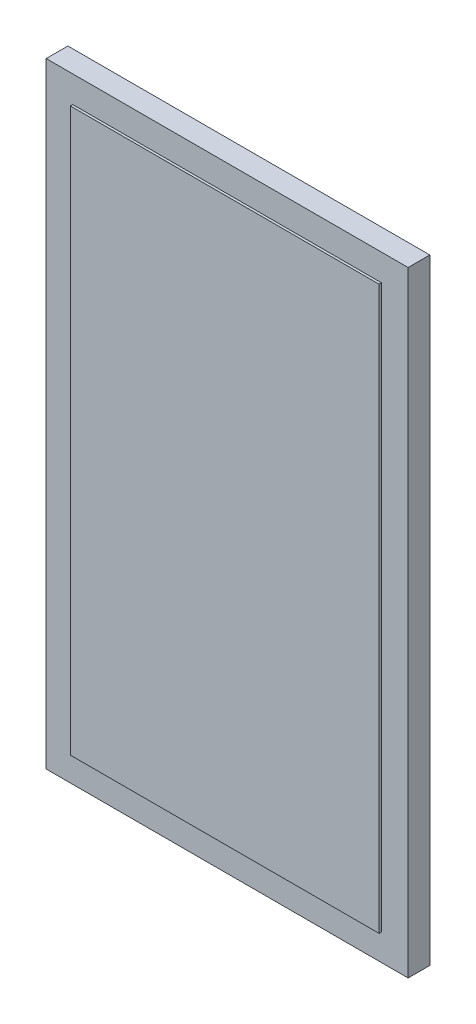
SolidWorks part; units mm, degrees
ref_plane "Plan de face" through (0, 0, 0) normal (0, 0, 1) x (1, 0, 0)
ref_plane "Plan de dessus" through (0, 0, 0) normal (0, 1, 0) x (1, 0, 0)
ref_plane "Plan de droite" through (0, 0, 0) normal (1, 0, 0) x (0, 0, -1)
sketch "Esquisse1" plane through (0, 0, 0) normal (0, 0, 1) x (1, 0, 0)
  line L1 (-75, 127.5) -> (75, 127.5)
  line L2 (-75, 127.5) -> (-75, -127.5)
  line L3 (-75, -127.5) -> (75, -127.5)
  line L4 (75, 127.5) -> (75, -127.5)
  line L5 (-75, 127.5) -> (75, -127.5) construction
  line L6 (-75, -127.5) -> (75, 127.5) construction
  point P0 (0, 0)
  dimension "D1" = 150
  dimension "D2" = 255
extrude "Boss.-Extru.1" add sketch "Esquisse1" along normal blind 10
sketch "Esquisse2" plane through (0, 0, 10) normal (0, 0, 1) x (1, 0, 0)
  line L1 (-75, 127.5) -> (75, 127.5)
  line L2 (-75, 127.5) -> (-75, -127.5)
  line L3 (-75, -127.5) -> (75, -127.5)
  line L4 (75, 127.5) -> (75, -127.5)
  line L5 (-75, 127.5) -> (75, -127.5) construction
  line L6 (-75, -127.5) -> (75, 127.5) construction
  line L7 (-64, 116.5) -> (64, 116.5)
  line L8 (-64, 116.5) -> (-64, -116.5)
  line L9 (-64, -116.5) -> (64, -116.5)
  line L10 (64, 116.5) -> (64, -116.5)
  line L11 (-64, 116.5) -> (64, -116.5) construction
  line L12 (-64, -116.5) -> (64, 116.5) construction
  point P0 (0, 0)
  point P7 (0, 0)
  dimension "D1" = 11
  dimension "D2" = 11
extrude "Enlèv. mat.-Extru.1" cut sketch "Esquisse2" against normal blind 1
